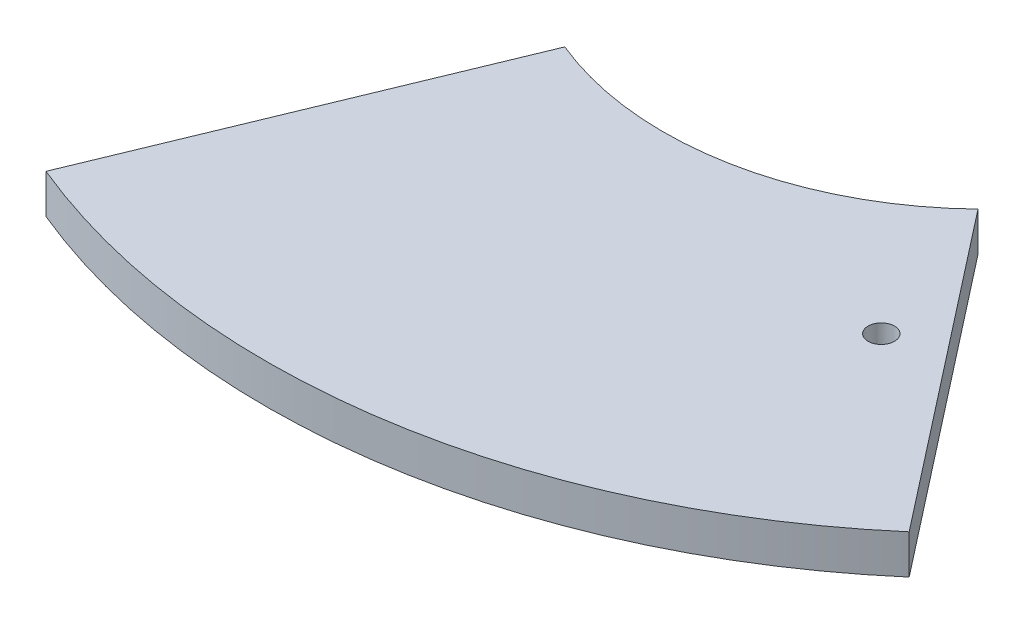
SolidWorks part; units mm, degrees
ref_plane "前视基准面" through (0, 0, 0) normal (0, 0, 1) x (1, 0, 0)
ref_plane "上视基准面" through (0, 0, 0) normal (0, 1, 0) x (1, 0, 0)
ref_plane "右视基准面" through (0, 0, 0) normal (1, 0, 0) x (0, 0, -1)
sketch "草图1" plane through (0, 0, 0) normal (0, 1, 0) x (1, 0, 0)
  circle A0 centre (0, 0) radius 210
  dimension "D1" = 420
extrude "凸台-拉伸1" add sketch "草图1" along normal blind 10
sketch "草图2" plane through (0, 10, 0) normal (0, 1, 0) x (1, 0, 0)
  circle A0 centre (0, 0) radius 75
  dimension "D1" = 150
extrude "切除-拉伸1" cut sketch "草图2" against normal blind 10
sketch "草图3" plane through (0, 10, 0) normal (0, 1, 0) x (1, 0, 0)
  line L0 (-218.1071, -133.4136) -> (-168.7855, -202.1496)
  line L1 (-218.1071, -133.4136) -> (-278.7239, 176.4685)
  line L2 (-278.7239, 176.4685) -> (-16.6419, 302.9796)
  line L3 (-16.6419, 302.9796) -> (429.7514, 108.172)
  line L4 (429.7514, 108.172) -> (267.2486, -202.1496)
  line L5 (267.2486, -202.1496) -> (64.6095, -313.7479)
  line L8 (-50, -50) -> (50, -50)
  line L10 (-168.7855, -202.1496) -> (-50, -50)
  line L11 (0, 0) -> (0, -152.1956) construction
  line L12 (168.7855, -202.1496) -> (50, -50)
  line L13 (168.7855, -202.1496) -> (64.6095, -313.7479)
  dimension "D3" = 50
sketch "草图4" plane through (0, 10, 0) normal (0, 1, 0) x (1, 0, 0)
  circle A0 centre (0, 0) radius 82.1974
extrude "切除-拉伸3" cut sketch "草图4" against normal blind 10
sketch "草图5" plane through (0, 10, 0) normal (0, 1, 0) x (1, 0, 0)
  circle A0 centre (0, 0) radius 183.0376
  circle A1 centre (0, 0) radius 232.5768
extrude "切除-拉伸4" cut sketch "草图5" against normal blind 10
extrude "切除-拉伸6" cut sketch "草图3" against normal blind 10
sketch "草图6" plane through (0, 10, 0) normal (0, 1, 0) x (1, 0, 0)
  line L0 (0, 0) -> (0, -233.4053)
  line L1 (0, -233.4053) -> (-177.2118, -160.7952)
  line L2 (-177.2118, -160.7952) -> (-110.7125, -38.2207)
  line L3 (-110.7125, -38.2207) -> (0, 0)
extrude "切除-拉伸7" cut sketch "草图6" against normal blind 10
sketch "草图7" plane through (0, 10, 0) normal (0, 1, 0) x (1, 0, 0)
  line L0 (0, -131.1613) -> (0, -190)
  line L1 (94.0105, -106.372) -> (123.6137, -144.2901)
  line L2 (0, -131.1613) -> (94.0105, -106.372)
  arc A0 (0, -190) -> (123.6137, -144.2901) centre (0, 0) ccw
  dimension "D1" = 380
extrude "凸台-拉伸2" add sketch "草图7" against normal blind 10
sketch "草图8" plane through (0, 10, 0) normal (0, 1, 0) x (1, 0, 0)
  circle A0 centre (72.2973, -98.9485) radius 3.3702
extrude "切除-拉伸9" cut sketch "草图8" against normal blind 10 contours A0
sketch "草图9" plane through (0, 0, 0) normal (0, -1, 0) x (1, 0, 0)
  line L0 (-72.5297, 175.6116) -> (-31.3776, 75.9728)
  line L1 (0, 190) -> (0, 82.1974)
  arc A0 (0, 82.1974) -> (-31.3776, 75.9728) centre (0, 0) ccw
  arc A1 (0, 190) -> (-72.5297, 175.6116) centre (0, 0) ccw
extrude "凸台-拉伸3" add sketch "草图9" against normal blind 10
sketch "草图10" plane through (0, 0, 0) normal (0, -1, 0) x (1, 0, 0)
  circle A0 centre (0, 0) radius 189.3466
  circle A1 centre (6.9282, 3.3795) radius 221.119
extrude "切除-拉伸10" cut sketch "草图10" against normal blind 20
sketch "草图11" plane through (0, 0, 0) normal (0, -1, 0) x (1, 0, 0)
  circle A0 centre (0, 0) radius 183.4832
  circle A1 centre (0, 17.7327) radius 238.0006
extrude "切除-拉伸11" cut sketch "草图11" against normal blind 20
